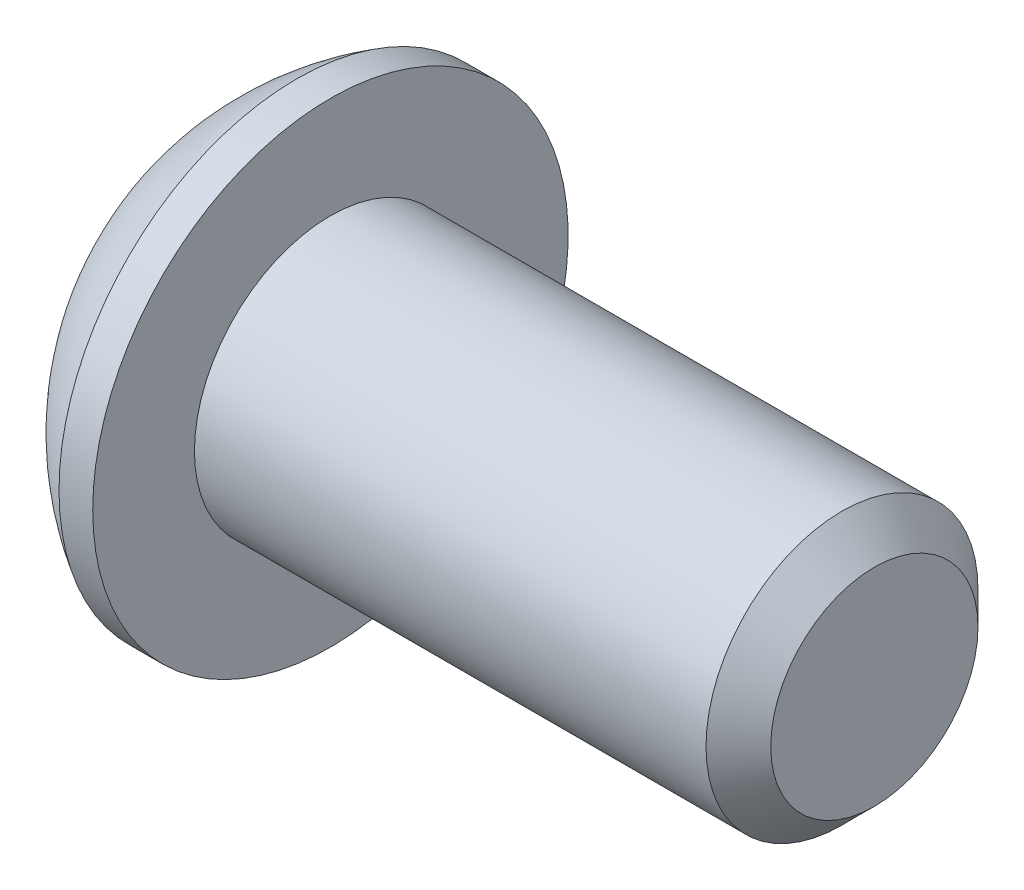
SolidWorks part; units mm, degrees
ref_plane "Plane1"
ref_plane "Plane2" through (0, 0, 0) normal (0, 1, 0) x (1, 0, 0)
ref_plane "Plane3" through (0, 0, 0) normal (1, 0, 0) x (0, 0, -1)
sketch "BodySke" plane through (0, 0, 0) normal (0, 0, 1) x (1, 0, 0)
  line L0 (16.0528, 0) -> (16.0528, 2.4193)
  line L1 (15.2971, 3.175) -> (3.3528, 3.175)
  line L2 (3.3528, 3.175) -> (3.3528, 5.5499)
  line L3 (3.3528, 5.5499) -> (2.5654, 5.5499)
  line L4 (0, 0) -> (101.6, 0) construction
  line L5 (3.3528, -5.5499) -> (2.5654, -5.5499) construction
  line L6 (55.6768, -3.175) -> (3.3528, -3.175) construction
  line L7 (16.0528, 0) -> (0, 0)
  line L8 (0, 2.775) -> (0, -2.775) construction
  line L9 (0, 0) -> (0, 2.775)
  line L10 (16.0528, 2.4193) -> (15.2971, 3.175)
  line L11 (16.0528, -2.4193) -> (15.2971, -3.175) construction
  line L12 (4.6228, 9.525) -> (4.6228, -3.175) construction
  line L13 (3.3528, 9.525) -> (3.3528, -3.175) construction
  arc A1 (0, 2.775) -> (2.5654, 5.5499) centre (5.7851, 0) cw
  dimension "Diameter" = 6.35
  dimension "Length" = 12.7
  dimension "Head_dia" = 11.0998
  dimension "D1" = 5.5499
  dimension "Head_ht" = 3.3528
  dimension "Head_side_ht" = 0.7874
  dimension "Minor_dia" = 4.8387
  dimension "Body_ch_ang" = 45
  dimension "Advance" = 1.27
  dimension "Thread_nom" = 12.7
revolve "BaseBody" add sketch "BodySke" angle 360 about L4
cosmetic thread "ThreadCosmetic" parameters "Thread_length"=11.43, "Thread_minor"=4.8387
sketch "Sketch2" plane through (0, 0, 0) normal (0, 0, 1) x (1, 0, 0)
  line L0 (0, 1.9812) -> (2.2098, 1.9812)
  line L1 (2.2098, 1.9812) -> (3.3536, 0)
  line L3 (3.3536, 0) -> (0, 0)
  line L4 (0, 0) -> (0, 1.9812)
  line L5 (0, -1.9812) -> (2.2098, -1.9812) construction
  line L6 (0, 0) -> (47.625, 0) construction
  dimension "D2" = 60
  dimension "PreBroach_depth" = 2.2098
  dimension "PreBroach_dia" = 3.9624
revolve "PreBroach" cut sketch "Sketch2" angle 360 about L6
sketch "Sketch3" plane through (0, 0, 0) normal (1, 0, 0) x (0, 0, -1)
  line L0 (-1.9812, -1.1438) -> (-1.9812, 1.1438)
  line L1 (-1.9812, 1.1438) -> (0, 2.2877)
  line L2 (0, 2.2877) -> (1.9812, 1.1438)
  line L3 (1.9812, 1.1438) -> (1.9812, -1.1438)
  line L4 (1.9812, -1.1438) -> (0, -2.2877)
  line L5 (0, -2.2877) -> (-1.9812, -1.1438)
  dimension "Hex_size" = 3.9624
  dimension "D3" = 3.9624
  dimension "D1" = 1.9812
  dimension "D2" = 1.9812
extrude "Hex" cut sketch "Sketch3" along normal blind 2.2098
sketch "Sketch4" plane through (0, 9.525, 0) normal (1, 0, 0) x (0, 0, -1)
  line L0 (0, -9.525) -> (2.3876, -9.525)
  line L1 (0, -9.525) -> (6.1484, -5.9752) construction
  line L2 (0, -9.525) -> (1.1938, -7.4573)
  line L3 (1.9883, -8.949) -> (2.2704, -8.7861)
  line L4 (1.493, -8.0911) -> (1.7751, -7.9282)
  arc A0 (1.9883, -8.949) -> (1.493, -8.0911) centre (0, -9.525) ccw
  arc A1 (2.3876, -9.525) -> (2.2704, -8.7861) centre (0, -9.525) ccw
  arc A2 (1.1938, -7.4573) -> (1.7751, -7.9282) centre (0, -9.525) cw
  dimension "Spline_n_dim" = 4.1402
  dimension "Spline_m_dim" = 4.7752
  dimension "D1" = 30
  dimension "D2" = 60
  dimension "Spline_p_dim" = 0.9906
  dimension "D3" = 0.4953
extrude "Spline" [suppressed] cut sketch "Sketch4" along normal blind 2.2098
pattern_circular "CirPattern1" [suppressed] count 6 every 60 about axis through (0, 0, 0) along (1, 0, 0)
sketch "ThdSchSke" plane through (0, 0, 0) normal (0, 0, 1) x (1, 0, 0)
  line L0 (4.6228, -2.4193) -> (4.0937, -3.175)
  line L1 (4.6228, -2.4193) -> (5.1519, -3.175)
  line L2 (5.1519, -3.175) -> (5.1519, -3.9688)
  line L3 (-3.175, 0) -> (5.1513, 0) construction
  line L5 (5.1519, -3.9688) -> (4.0937, -3.9688)
  line L6 (4.0937, -3.9688) -> (4.0937, -3.175)
  dimension "Diameter" = 6.35
  dimension "Thread_minor" = 4.8387
  dimension "SideAngle" = 55
  dimension "VeeAngle" = 70
  dimension "Overcut" = 7.9375
  dimension "Start" = 4.6228
revolve "ThreadSchematic" [suppressed] cut sketch "ThdSchSke" angle 360 about L3
pattern_linear "ThdSchPat" [suppressed]
equation "\"D1@BodySke\" = \"Head_dia@BodySke\" * .5"
equation "\"Thread_minor@ThreadCosmetic\" = \"Minor_dia@BodySke\""
equation "\"D1@Sketch3\" = \"Hex_size@Sketch3\" / 2"
equation "\"D2@Sketch3\" = \"D1@Sketch3\""
equation "\"D3@Sketch3\" = \"Hex_size@Sketch3\""
equation "\"D3@Sketch4\" = \"Spline_p_dim@Sketch4\" / 2"
equation "\"D1@Sketch4\" = \"D2@Sketch4\" / 2"
equation "\"Thread_length@ThreadCosmetic\" = ((sgn( (\"Length@BodySke\" - \"Advance@BodySke\" ) - \"Thread_nom@BodySke\" )-1)*( (\"Length@BodySke\" - \"Advance@BodySke\" ) - \"Thread_nom@BodySke\" ))/-2+ \"Thread_nom@BodySke\""
equation "\"Thread_minor@ThdSchSke\" = \"Minor_dia@BodySke\""
equation "\"Diameter@ThdSchSke\" = \"Diameter@BodySke\""
equation "\"Overcut@ThdSchSke\" = \"Diameter@BodySke\" * 1.25"
equation "\"Start@ThdSchSke\" = \"Head_ht@BodySke\" + \"Length@BodySke\" - \"Thread_length@ThreadCosmetic\"  '---Non-countersunk---"
equation "\"Num_threads@ThdSchPat\" = int( \"Thread_length@ThreadCosmetic\" / \"Advance@BodySke\" + 0.999 )  + 1"
equation "\"Advance@ThdSchPat\" = \"Thread_length@ThreadCosmetic\" /  (\"Num_threads@ThdSchPat\" - 1) 'relax it"
equation "\"Num_threads@ThdSchPat\" = \"Num_threads@ThdSchPat\" - sgn( \"Num_threads@ThdSchPat\" - 1) '---chamfered tips only---"
